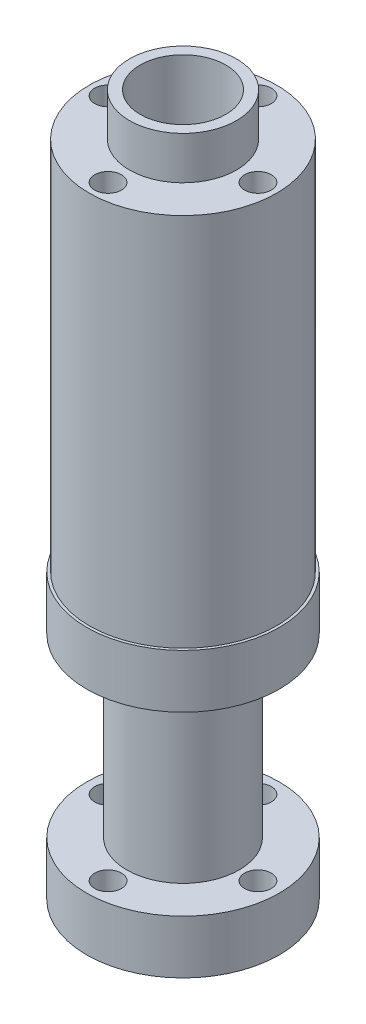
SolidWorks part; units mm, degrees
ref_plane "前视基准面" through (0, 0, 0) normal (0, 0, 1) x (1, 0, 0)
ref_plane "上视基准面" through (0, 0, 0) normal (0, 1, 0) x (1, 0, 0)
ref_plane "右视基准面" through (0, 0, 0) normal (1, 0, 0) x (0, 0, -1)
sketch "草图1" plane through (0, 0, 0) normal (0, 1, 0) x (1, 0, 0)
  circle A0 centre (0, 0) radius 9
  circle A1 centre (0, 0) radius 4
  dimension "D1" = 18
  dimension "D2" = 8
extrude "凸台-拉伸1" add sketch "草图1" along normal blind 5
sketch "草图3" plane through (0, 0, 0) normal (0, -1, 0) x (1, 0, 0)
  line L0 (-9, 0) -> (9, 0) construction
  line L1 (0, 9) -> (0, -9) construction
  circle A0 centre (0, 0) radius 9 construction
  point P7 (-7, 0)
  point P8 (7, 0)
  point P9 (0, 7)
  point P10 (0, -7)
  dimension "D1" = 14
  dimension "D2" = 14
hole_wizard "M3 螺纹孔1" positions "草图4" profile "草图5" tap size "M3" standard "GB" end condition through all
sketch "草图4" plane through (0, 0, 0) normal (0, -1, 0) x (-1, 0, 0)
  point P0 (7, 0)
  point P3 (0, -7)
  point P6 (-7, 0)
  point P9 (0, 7)
sketch "草图5" plane through (-7, 0, 0) normal (1, 0, 0) x (0, 0, -1)
  line L0 (0, 0) -> (0, 5)
  line L1 (0, 5) -> (1.25, 5)
  line L2 (1.25, 5) -> (1.25, 0)
  line L5 (1.25, 0) -> (0, 0)
  line L11 (0, -6.35) -> (0, 107.95) construction
  dimension "通孔螺纹孔钻头直径" = 2.5
  dimension "通孔螺纹孔钻头深度" = 5
cosmetic thread "孔螺蚊线1" parameters "D2"=3
cosmetic thread "孔螺蚊线2" parameters "D2"=3
cosmetic thread "孔螺蚊线3" parameters "D2"=3
cosmetic thread "孔螺蚊线4" parameters "D2"=3
sketch "草图6" plane through (0, 5, 0) normal (0, 1, 0) x (1, 0, 0)
  circle A0 centre (0, 0) radius 5.25
  dimension "D1" = 10.5
extrude "凸台-拉伸2" add sketch "草图6" along normal blind 16.5
sketch "草图7" plane through (0, 21.5, 0) normal (0, 1, 0) x (1, 0, 0)
  circle A0 centre (0, 0) radius 9
extrude "凸台-拉伸3" add sketch "草图7" along normal blind 5
sketch "草图8" plane through (0, 26.5, 0) normal (0, 1, 0) x (1, 0, 0)
  circle A0 centre (0, 0) radius 8.75
  dimension "D1" = 17.5
extrude "凸台-拉伸4" add sketch "草图8" along normal blind 35
sketch "草图9" plane through (0, 61.5, 0) normal (0, 1, 0) x (1, 0, 0)
  line L0 (-9, 0) -> (9, 0) construction
  line L1 (0, 9) -> (0, -9) construction
  circle A0 centre (0, 0) radius 9 construction
  point P7 (-7, 0)
  point P8 (0, 7)
  point P9 (0, -7)
  point P10 (7, 0)
  dimension "D1" = 14
  dimension "D2" = 14
hole_wizard "M3 螺纹孔2" positions "草图10" profile "草图11" tap size "M3" standard "GB"
sketch "草图10" plane through (0, 61.5, 0) normal (0, 1, 0) x (1, 0, 0)
  point P0 (0, 7)
  point P3 (-7, 0)
  point P6 (7, 0)
  point P9 (0, -7)
sketch "草图11" plane through (0, 61.5, -7) normal (1, 0, 0) x (0, 0, 1)
  line L0 (0, 0) -> (0, 10.7511)
  line L1 (0, 10.7511) -> (1.25, 10)
  line L2 (1.25, 10) -> (1.25, 0)
  line L5 (1.25, 0) -> (0, 0)
  line L10 (0, 10.7511) -> (-1.25, 10) construction
  line L11 (0, -6.35) -> (0, 107.95) construction
  dimension "螺纹孔钻头直径" = 2.5
  dimension "螺纹孔钻头深度" = 10
  dimension "导头角度" = 118
cosmetic thread "孔螺蚊线5" parameters "D1"=10, "D2"=3
cosmetic thread "孔螺蚊线6" parameters "D1"=10, "D2"=3
cosmetic thread "孔螺蚊线7" parameters "D1"=10, "D2"=3
cosmetic thread "孔螺蚊线8" parameters "D1"=10, "D2"=3
sketch "草图12" plane through (0, 61.5, 0) normal (0, 1, 0) x (1, 0, 0)
  circle A0 centre (0, 0) radius 5
  dimension "D1" = 10
extrude "凸台-拉伸5" add sketch "草图12" along normal blind 4
sketch "草图13" plane through (0, 5, 0) normal (0, -1, 0) x (1, 0, 0)
  circle A0 centre (0, 0) radius 4
  dimension "D1" = 8
extrude "切除-拉伸1" cut sketch "草图13" against normal blind 165
sketch "草图14" plane through (0, 0, 0) normal (0, -1, 0) x (1, 0, 0)
  circle A0 centre (0, 0) radius 4
  circle A1 centre (0, 0) radius 5
  dimension "D1" = 10
  dimension "D2" = 8
extrude "凸台-拉伸6" add sketch "草图14" along normal blind 2
fillet "圆角1" radius 2 1 edges at (0, 21.5, 5.25)
